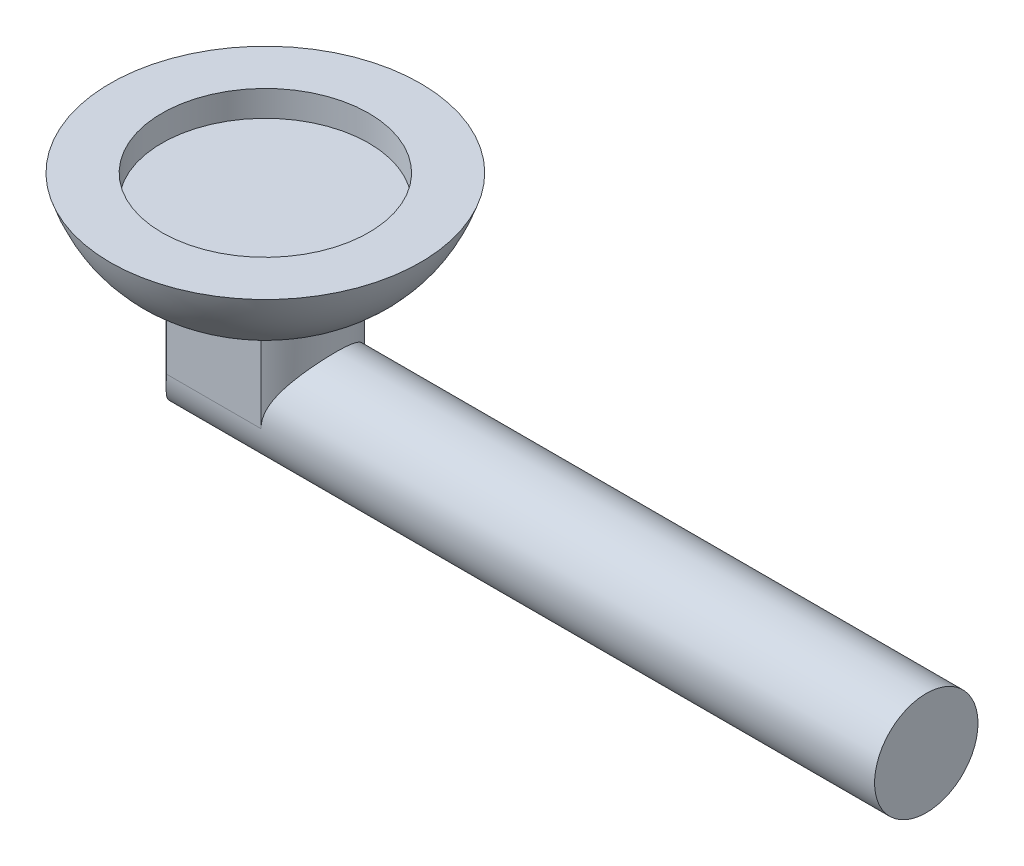
SolidWorks part; units mm, degrees
material "1060 Alloy"
ref_plane "Front Plane" through (0, 0, 0) normal (0, 0, 1) x (1, 0, 0)
ref_plane "Top Plane" through (0, 0, 0) normal (0, 1, 0) x (1, 0, 0)
ref_plane "Right Plane" through (0, 0, 0) normal (1, 0, 0) x (0, 0, -1)
sketch "Sketch1" plane through (0, 0, 0) normal (0, 0, 1) x (1, 0, 0)
  line L0 (-9.915, 23.2402) -> (-9.915, -36.4262) construction
  line L1 (28.185, 23.2402) -> (-9.915, 23.2402)
  line L2 (7.3051, 1.6738) -> (7.3051, -36.4262)
  line L3 (7.3051, -36.4262) -> (-9.915, -36.4262)
  line L4 (-9.915, 23.2402) -> (-9.915, -36.4262)
  spline S0 degree 3 poles (7.3051, 1.6738) (17.6889, 5.057) (24.6489, 12.2458) (28.185, 23.2402) knots 0.179472 0.179472 0.179472 0.179472 1 1 1 1
  dimension "D1" = 38.1
  dimension "D2" = 38.1
revolve "Revolve1" add sketch "Sketch1" angle 360 about L0
ref_plane "Plane1" through (101.6, 0, 0) normal (1, 0, 0) x (0, 0, -1)
sketch "Sketch2" plane through (101.6, 0, 0) normal (1, 0, 0) x (0, 0, -1)
  circle A0 centre (0, -18.9984) radius 12.7
  dimension "D1" = 25.4
extrude "Boss-Extrude1" add sketch "Sketch2" against normal blind 101.6 and the other way blind 50.8
sketch "Sketch3" plane through (101.6, 0, 0) normal (1, 0, 0) x (0, 0, -1)
  line L0 (17.2201, -18.9984) -> (17.2201, -36.4262)
  line L1 (17.2201, -36.4262) -> (-17.2201, -36.4262)
  line L2 (-17.2201, -36.4262) -> (-17.2201, -18.9984)
  line L3 (-12.7, -18.9984) -> (-12.7, 1.6738)
  line L4 (-17.2201, 1.6738) -> (17.2201, 1.6738) construction
  line L5 (-12.7, 1.6738) -> (-17.2201, 1.6738)
  line L6 (-17.2201, 1.6738) -> (-17.2201, -18.9984)
  line L7 (12.7, -18.9984) -> (12.7, 1.6738)
  line L8 (12.7, 1.6738) -> (17.2201, 1.6738)
  line L9 (17.2201, 1.6738) -> (17.2201, -18.9984)
  circle A0 centre (0, -18.9984) radius 12.7
  dimension "D1" = 25.4
extrude "Cut-Extrude2" cut sketch "Sketch3" against normal through all contours A0 L3 L5 L6 L2 L1 L0 L9 L8 L7
ref_plane "Plane2" through (0, 23.2402, 0) normal (0, 1, 0) x (1, 0, 0)
sketch "Sketch4" plane through (0, 23.2402, 0) normal (0, 1, 0) x (1, 0, 0)
  circle A0 centre (-9.915, 0) radius 25.4
  dimension "D1" = 50.8
extrude "Cut-Extrude3" cut sketch "Sketch4" against normal blind 6.35
